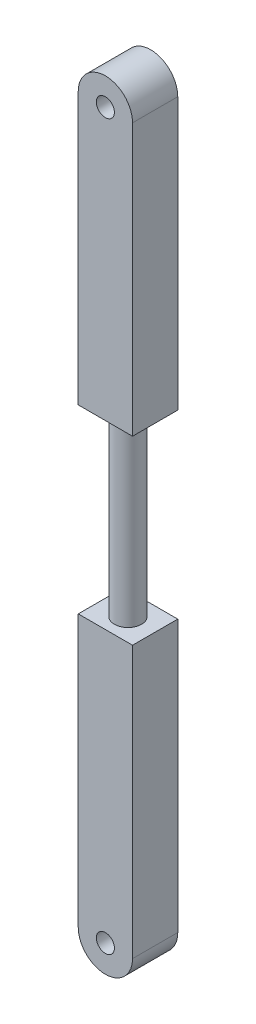
SolidWorks part; units mm, degrees
ref_plane "前视基准面" through (0, 0, 0) normal (0, 0, 1) x (1, 0, 0)
ref_plane "上视基准面" through (0, 0, 0) normal (0, 1, 0) x (1, 0, 0)
ref_plane "右视基准面" through (0, 0, 0) normal (1, 0, 0) x (0, 0, -1)
other "Configuration Table"
sketch "草图1" plane through (0, 0, 0) normal (0, 0, 1) x (1, 0, 0)
  line L0 (0, 0) -> (0, -80) construction
  line L1 (3, 0) -> (3, -80)
  line L2 (-3, 0) -> (-3, -80)
  arc A0 (3, 0) -> (-3, 0) centre (0, 0) ccw
  arc A1 (-3, -80) -> (3, -80) centre (0, -80) ccw
  circle A2 centre (0, 0) radius 1
  circle A3 centre (0, -80) radius 1
  point P3 (0, -40)
  point P12 (0, 0)
  dimension "D3" = 2
  dimension "D1" = 80
  dimension "D2" = 6
extrude "凸台-拉伸1" add sketch "草图1" along normal mid plane 5
move or copy body "实体-移动/复制1" bodies to move or copy 107 copy no translate (0, 40, 0)
sketch "草图4" plane through (0, 0, 0) normal (0, 1, 0) x (1, 0, 0)
  circle A0 centre (0, 0) radius 1.5
  circle A1 centre (0, 0) radius 5.3418
  dimension "D1" = 3
extrude "切除-拉伸2" cut sketch "草图4" against normal mid plane 20
